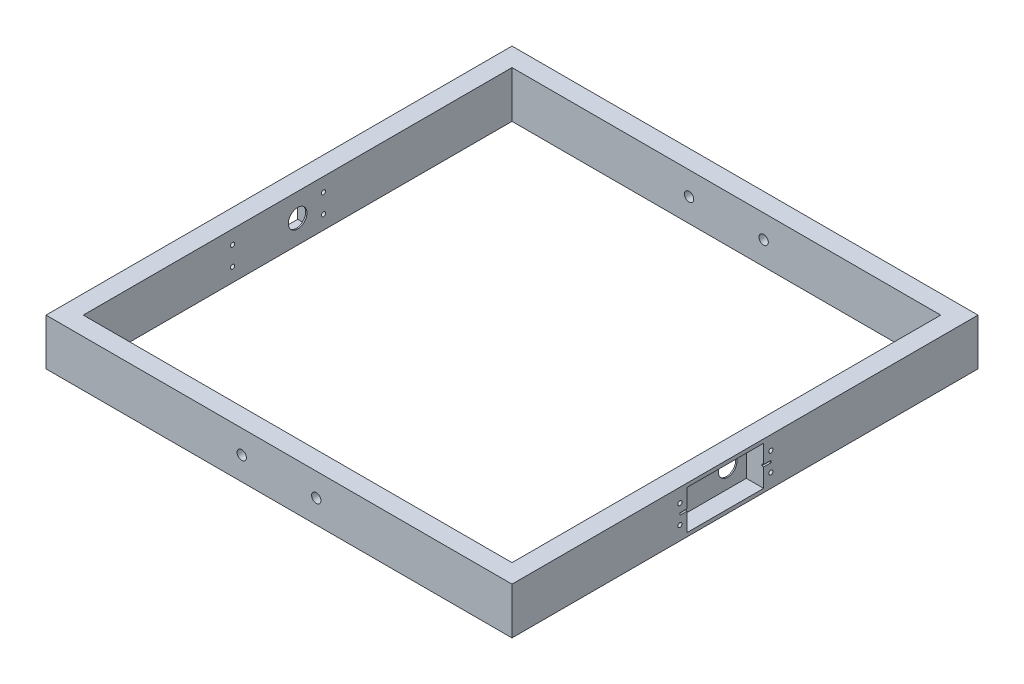
SolidWorks part; units mm, degrees
ref_plane "Front Plane" through (0, 0, 0) normal (0, 0, 1) x (1, 0, 0)
ref_plane "Top Plane" through (0, 0, 0) normal (0, 1, 0) x (1, 0, 0)
ref_plane "Right Plane" through (0, 0, 0) normal (1, 0, 0) x (0, 0, -1)
sketch "Sketch1" plane through (0, 0, 0) normal (0, 1, 0) x (1, 0, 0)
  line L1 (-125, -125) -> (125, -125)
  line L2 (-125, -125) -> (-125, 125)
  line L3 (-125, 125) -> (125, 125)
  line L4 (125, -125) -> (125, 125)
  line L5 (-125, -125) -> (125, 125) construction
  line L6 (-125, 125) -> (125, -125) construction
  point P0 (0, 0)
  dimension "D1" = 250
extrude "Boss-Extrude1" add sketch "Sketch1" along normal blind 25
sketch "Sketch2" plane through (0, 25, 0) normal (0, 1, 0) x (1, 0, 0)
  line L0 (125, 125) -> (-125, 125) construction
  line L1 (-115, -115) -> (115, -115)
  line L2 (-115, -115) -> (-115, 115)
  line L3 (-115, 115) -> (115, 115)
  line L4 (115, -115) -> (115, 115)
  line L5 (-115, -115) -> (115, 115) construction
  line L6 (-115, 115) -> (115, -115) construction
  point P0 (0, 0)
  dimension "D1" = 10
extrude "Cut-Extrude1" cut sketch "Sketch2" against normal blind 25
sketch "Sketch19" plane through (-125, 0, 0) normal (-1, 0, 0) x (0, 0, 1)
  line L0 (-125, 25) -> (-125, 0) construction
  line L1 (-10, 23) -> (31, 23)
  line L2 (-10, 23) -> (-10, 2)
  line L3 (-10, 2) -> (31, 2)
  line L4 (31, 23) -> (31, 2)
  line L5 (-10, 23) -> (31, 2) construction
  line L6 (-10, 2) -> (31, 23) construction
  line L7 (-125, 25) -> (125, 25) construction
  point P0 (10.5, 12.5)
  point P7 (-125, 12.5)
  point P10 (0, 25)
  dimension "D1" = 41
  dimension "D2" = 21
  dimension "D3" = 10
extrude "Cut-Extrude10" cut sketch "Sketch19" against normal blind 9.3
sketch "Sketch20" plane through (-115.7, 0, 0) normal (-1, 0, 0) x (0, 0, 1)
  line L0 (-10, 23) -> (-10, 2) construction
  circle A0 centre (0, 12.5) radius 5
  point P4 (-10, 12.5)
  dimension "D1" = 10
  dimension "D2" = 10
extrude "Cut-Extrude11" cut sketch "Sketch20" against normal blind 9.3
sketch "Sketch23" plane through (-125, 0, 0) normal (-1, 0, 0) x (0, 0, 1)
  line L0 (-10, 23) -> (-10, 2) construction
  line L1 (35, 11.95) -> (-14, 11.95)
  line L2 (35, 11.95) -> (35, 13.05)
  line L3 (35, 13.05) -> (-14, 13.05)
  line L4 (-14, 11.95) -> (-14, 13.05)
  line L5 (35, 11.95) -> (-14, 13.05) construction
  line L6 (35, 13.05) -> (-14, 11.95) construction
  line L7 (31, 23) -> (-10, 23) construction
  point P0 (10.5, 12.5)
  point P10 (10.5, 23)
  point P11 (-10, 12.5)
  dimension "D1" = 1.1
  dimension "D2" = 4
extrude "Cut-Extrude14" cut sketch "Sketch23" against normal blind 1
ref_plane "Plane5" through (0, 0, 10.5) normal (0, 0, 1) x (1, 0, 0)
ref_plane "Plane6" through (0, 12.5, 0) normal (0, 1, 0) x (1, 0, 0)
sketch "Sketch21" plane through (-125, 0, 0) normal (-1, 0, 0) x (0, 0, 1)
  line L0 (-10, 23) -> (-10, 2) construction
  circle A0 centre (-13.9, 17.6) radius 1.125
  point P4 (-10, 12.5)
  dimension "D3" = 2.25
  dimension "D1" = 3.9
  dimension "D2" = 5.1
extrude "Cut-Extrude12" cut sketch "Sketch21" against normal blind 10
mirror "Mirror1" about plane through (0, 0, 10.5) normal (0, 0, 1) of "Cut-Extrude12" second plane through (0, 12.5, 0) second plane normal (0, 1, 0)
ref_plane "Plane7" through (0, 0, 0) normal (-1, 0, 0) x (0, 0, 1)
mirror "Mirror2" about plane through (0, 0, 0) normal (-1, 0, 0) of "Cut-Extrude14", "Cut-Extrude10", "Cut-Extrude11", "Cut-Extrude12", "Mirror1"
sketch "Sketch22" plane through (0, 0, 125) normal (0, 0, 1) x (1, 0, 0)
  line L0 (-125, 25) -> (-125, 0) construction
  circle A0 centre (-20, 12.5) radius 2.5
  circle A1 centre (20, 12.5) radius 2.5
  point P9 (-125, 12.5)
  dimension "D1" = 5
  dimension "D2" = 40
  dimension "D3" = 20
extrude "Cut-Extrude13" cut sketch "Sketch22" against normal through all
